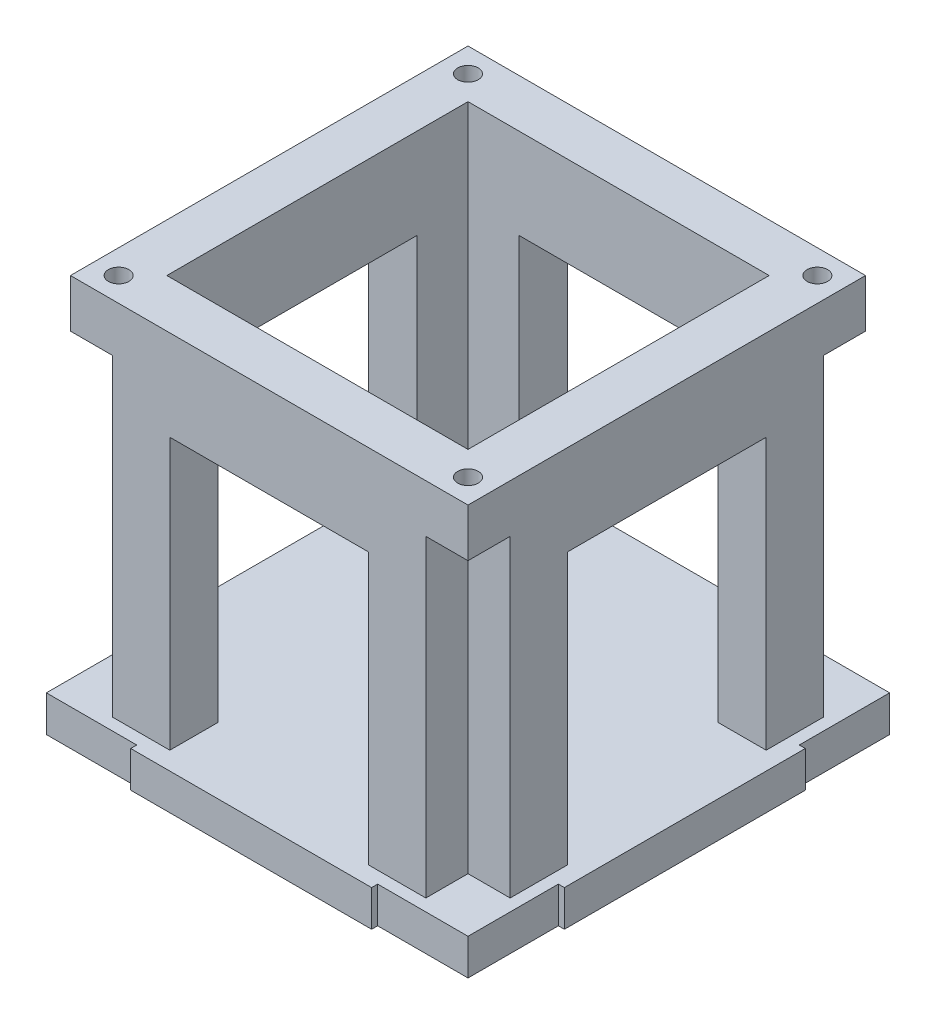
SolidWorks part; units mm, degrees
ref_plane "Front Plane" through (0, 0, 0) normal (0, 0, 1) x (1, 0, 0)
ref_plane "Top Plane" through (0, 0, 0) normal (0, 1, 0) x (1, 0, 0)
ref_plane "Right Plane" through (0, 0, 0) normal (1, 0, 0) x (0, 0, -1)
sketch "Sketch1" plane through (0, 0, 0) normal (0, 1, 0) x (1, 0, 0)
  line L4 (-57.707, 0) -> (67.0064, 0) construction
  line L8 (0, -63.8217) -> (0, 54.8025) construction
  line L24 (-20, 36) -> (20, 36)
  line L25 (-36, 20) -> (-36, -20)
  line L26 (-20, 36) -> (-20, 35)
  line L27 (-20, 35) -> (-35, 35)
  line L28 (-35, 35) -> (-35, 20)
  line L29 (-35, 20) -> (-36, 20)
  line L30 (-35, -20) -> (-36, -20)
  line L31 (-35, -35) -> (-35, -20)
  line L32 (-20, -35) -> (-35, -35)
  line L33 (-20, -36) -> (-20, -35)
  line L34 (-20, -36) -> (20, -36)
  line L35 (20, -36) -> (20, -35)
  line L36 (20, -35) -> (35, -35)
  line L37 (35, -35) -> (35, -20)
  line L38 (35, -20) -> (36, -20)
  line L39 (35, 20) -> (36, 20)
  line L40 (35, 35) -> (35, 20)
  line L41 (20, 35) -> (35, 35)
  line L42 (20, 36) -> (20, 35)
  line L43 (36, 20) -> (36, -20)
  point P9 (-36, 0)
  point P11 (0, 36)
  point P14 (36, 0)
  point P15 (0, -36)
  point P16 (0, 36)
  point P19 (-36, 0)
  point P21 (0, 36)
  point P24 (0, -36)
  point P25 (0, 36)
  point P26 (-36, 0)
  point P28 (0, -36)
  point P37 (0, 36)
  dimension "D1" = 1
  dimension "D2" = 15
  dimension "D3" = 40
extrude "Boss-Extrude1" add sketch "Sketch1" against normal blind 6
sketch "Sketch2" plane through (0, 0, 0) normal (0, 1, 0) x (1, 0, 0)
  line L1 (-33, -33) -> (33, -33)
  line L2 (-33, -33) -> (-33, 33)
  line L3 (-33, 33) -> (33, 33)
  line L4 (33, -33) -> (33, 33)
  line L5 (-33, -33) -> (33, 33) construction
  line L6 (-33, 33) -> (33, -33) construction
  line L7 (-25, -25) -> (25, -25)
  line L8 (-25, -25) -> (-25, 25)
  line L9 (-25, 25) -> (25, 25)
  line L10 (25, -25) -> (25, 25)
  line L11 (-25, -25) -> (25, 25) construction
  line L12 (-25, 25) -> (25, -25) construction
  circle A0 centre (29, 29) radius 1.705
  circle A1 centre (-29, 29) radius 1.705
  circle A2 centre (29, -29) radius 1.705
  circle A3 centre (-29, -29) radius 1.705
  point P0 (0, 0)
  point P6 (0, 0)
  dimension "D1" = 3.41
  dimension "D5" = 4
  dimension "D6" = 4
  dimension "D7" = 4
  dimension "D8" = 4
  dimension "D2" = 8
  dimension "D3" = 50
  dimension "D4" = 50
extrude "Boss-Extrude2" add sketch "Sketch2" along normal blind 60
sketch "Sketch4" plane through (0, 0, 0) normal (0, 1, 0) x (1, 0, 0)
  line L0 (0, -40.6846) -> (0, 40.6846) construction
  line L17 (-33, 33) -> (-26, 33)
  line L18 (-33, 33) -> (-33, 26)
  line L19 (-33, 26) -> (-26, 26)
  line L20 (-26, 33) -> (-26, 26)
  line L21 (26, 33) -> (26, 26)
  line L22 (33, 26) -> (26, 26)
  line L23 (33, 33) -> (33, 26)
  line L24 (33, 33) -> (26, 33)
  line L25 (-43.4188, 0) -> (49.0977, 0) construction
  line L26 (33, -33) -> (26, -33)
  line L27 (33, -33) -> (33, -26)
  line L28 (33, -26) -> (26, -26)
  line L29 (26, -33) -> (26, -26)
  line L30 (-26, -33) -> (-26, -26)
  line L31 (-33, -26) -> (-26, -26)
  line L32 (-33, -33) -> (-33, -26)
  line L33 (-33, -33) -> (-26, -33)
  point P11 (0, 0)
  dimension "D1" = 1
  dimension "D2" = 1
extrude "Cut-Extrude2" cut sketch "Sketch4" along normal blind 52
sketch "Sketch5" plane through (0, 0, 0) normal (0, 1, 0) x (1, 0, 0)
  line L0 (0, -7.0297) -> (0, 37.115) construction
  line L1 (16.5, 33) -> (-16.5, 33)
  line L2 (26, 33) -> (-26, 33) construction
  line L3 (-16.5, 33) -> (-16.5, 25)
  line L4 (25, 25) -> (-25, 25) construction
  line L5 (-16.5, 25) -> (16.5, 25)
  line L6 (16.5, 33) -> (16.5, 25)
  line L7 (-46.8976, 0) -> (51.2236, 0) construction
  line L8 (16.5, -33) -> (16.5, -25)
  line L9 (-16.5, -25) -> (16.5, -25)
  line L10 (-16.5, -33) -> (-16.5, -25)
  line L11 (16.5, -33) -> (-16.5, -33)
  line L12 (25, -16.5) -> (25, 16.5)
  line L13 (25, -25) -> (25, 25) construction
  line L14 (25, -25) -> (25, 25) construction
  line L15 (25, 16.5) -> (33, 16.5)
  line L16 (33, -26) -> (33, 26) construction
  line L17 (33, 16.5) -> (33, -16.5)
  line L18 (25, -16.5) -> (33, -16.5)
  line L19 (-25, -16.5) -> (-33, -16.5)
  line L20 (-33, 16.5) -> (-33, -16.5)
  line L21 (-25, 16.5) -> (-33, 16.5)
  line L22 (-25, -16.5) -> (-25, 16.5)
  point P12 (0, 25)
  point P13 (0, 33)
  point P15 (0, -33)
  point P16 (0, -25)
  point P21 (-25, 0)
  point P32 (33, 0)
  point P33 (25, 0)
  point P34 (-33, 0)
  dimension "D1" = 33
  dimension "D2" = 33
extrude "Cut-Extrude3" cut sketch "Sketch5" along normal blind 45
